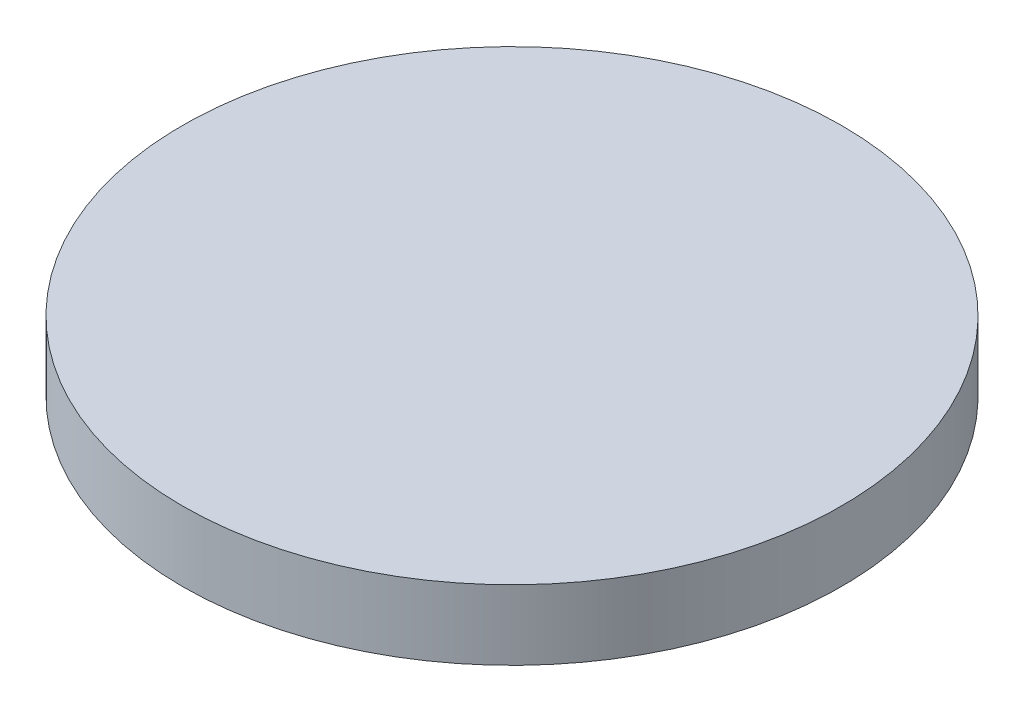
SolidWorks part; units mm, degrees
material "PTFE (general)"
ref_plane "Front Plane" through (0, 0, 0) normal (0, 0, 1) x (1, 0, 0)
ref_plane "Top Plane" through (0, 0, 0) normal (0, 1, 0) x (1, 0, 0)
ref_plane "Right Plane" through (0, 0, 0) normal (1, 0, 0) x (0, 0, -1)
sketch "Sketch1" plane through (0, 0, 0) normal (0, 1, 0) x (1, 0, 0)
  circle A0 centre (0, 0) radius 7.493
  dimension "D1" = 14.986
extrude "Extrude1" add sketch "Sketch1" along normal blind 1.5875
other "Freeze***"
